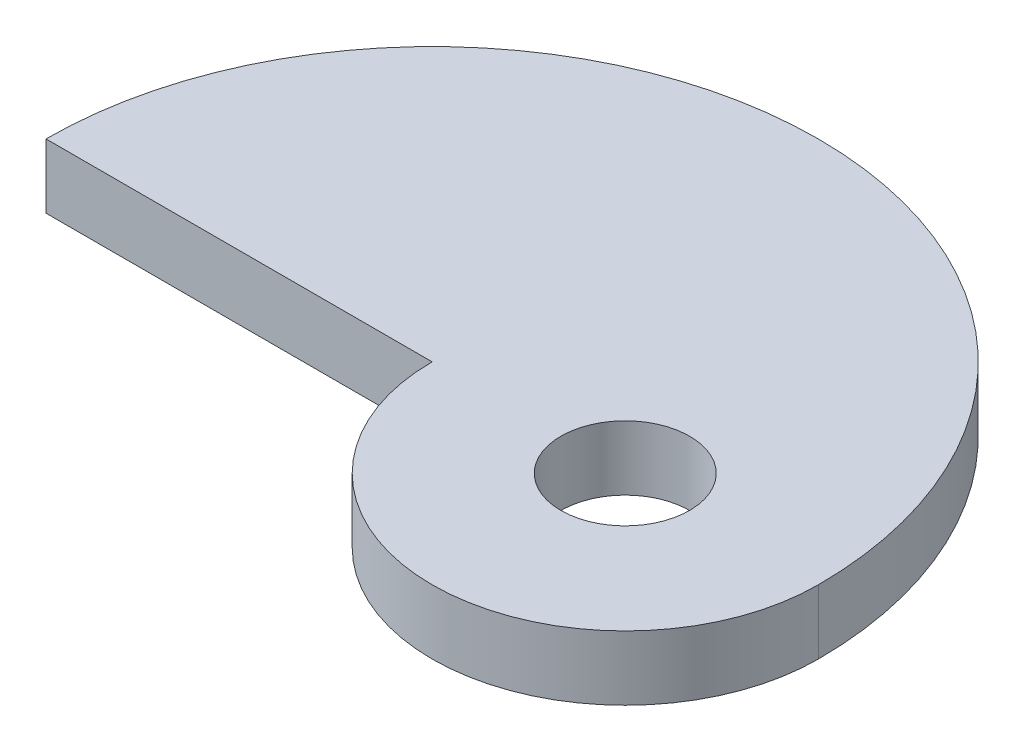
SolidWorks part; units mm, degrees
material "6061 Alloy"
ref_plane "Front Plane" through (0, 0, 0) normal (0, 0, 1) x (1, 0, 0)
ref_plane "Top Plane" through (0, 0, 0) normal (0, 1, 0) x (1, 0, 0)
ref_plane "Right Plane" through (0, 0, 0) normal (1, 0, 0) x (0, 0, -1)
sketch "Sketch2" plane through (0, 0, 0) normal (0, 1, 0) x (1, 0, 0)
  line L0 (0, 0) -> (-38.1, 0)
  line L1 (0, -19.05) -> (19.05, -19.05)
  line L2 (0, -19.05) -> (0, 0)
  line L3 (0, 0) -> (19.05, 0)
  line L4 (19.05, -19.05) -> (19.05, 0)
  line L5 (19.05, 0) -> (38.1, 0)
  line L6 (19.05, 0) -> (19.05, -19.05)
  line L7 (19.05, -19.05) -> (38.1, -19.05)
  line L8 (38.1, 0) -> (38.1, -19.05)
  line L9 (0, 0) -> (38.1, 0)
  line L10 (0, 0) -> (0, 38.1)
  line L11 (0, 38.1) -> (38.1, 38.1)
  line L12 (38.1, 0) -> (38.1, 38.1)
  line L13 (0, 38.1) -> (-38.1, 38.1)
  line L14 (0, 38.1) -> (0, 0)
  line L15 (0, 0) -> (-38.1, 0)
  line L16 (-38.1, 38.1) -> (-38.1, 0)
  arc A0 (0, 0) -> (19.05, -19.05) centre (19.05, 0) ccw
  arc A1 (19.05, -19.05) -> (38.1, 0) centre (19.05, 0) ccw
  arc A2 (38.1, 0) -> (0, 38.1) centre (0, 0) ccw
  arc A3 (0, 38.1) -> (-38.1, 0) centre (0, 0) ccw
  dimension "D1" = 19.05
  dimension "D2" = 19.05
  dimension "D3" = 19.05
  dimension "D4" = 19.05
  dimension "D5" = 38.1
  dimension "D6" = 38.1
  dimension "D7" = 38.1
  dimension "D8" = 38.1
extrude "Boss-Extrude2" add sketch "Sketch2" along normal blind 6.35 contours L10 A3 L0 | L5 A2 L10 L3 | L4 A1 L5 | L3 A0 L4
sketch "Sketch3" plane through (0, 6.35, 0) normal (0, 1, 0) x (1, 0, 0)
  circle A0 centre (19.05, 0) radius 6.35
  dimension "D1" = 12.7
  dimension "D2" = 19.05
extrude "Cut-Extrude1" cut sketch "Sketch3" against normal blind 6.35
